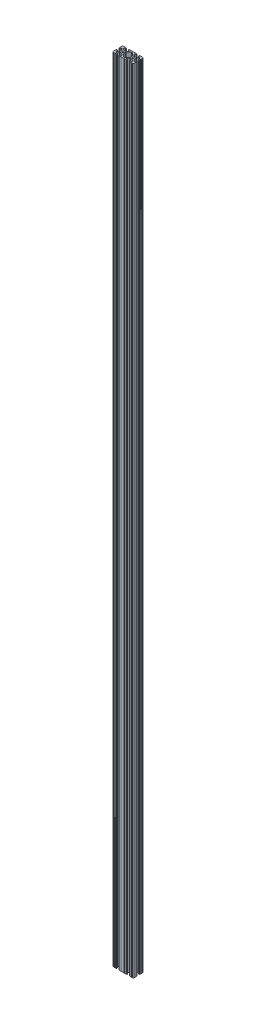
SolidWorks part; units mm, degrees
ref_plane "Piano frontale" through (0, 0, 0) normal (0, 0, 1) x (1, 0, 0)
ref_plane "Piano superiore" through (0, 0, 0) normal (0, 1, 0) x (1, 0, 0)
ref_plane "Piano destro" through (0, 0, 0) normal (1, 0, 0) x (0, 0, -1)
ref_plane "Piano1" through (0, 101.6, 0) normal (0, 1, 0) x (1, 0, 0)
sketch "Schizzo1" plane through (0, 101.6, 0) normal (0, 1, 0) x (1, 0, 0)
  line L0 (38.2382, -84.836) -> (37.9618, -84.836)
  line L1 (36.1657, -84.0921) -> (26.5503, -74.4767)
  line L2 (25.8064, -72.6806) -> (25.8064, -67.0194)
  line L3 (26.5503, -65.2233) -> (36.1657, -55.6079)
  line L4 (37.9618, -54.864) -> (38.2382, -54.864)
  line L5 (40.0343, -55.6079) -> (49.6497, -65.2233)
  line L6 (50.3936, -67.0194) -> (50.3936, -72.6806)
  line L7 (49.6497, -74.4767) -> (40.0343, -84.0921)
  line L8 (65.5208, -50.8) -> (62.992, -50.8)
  line L9 (61.214, -52.578) -> (61.214, -53.086)
  line L10 (62.992, -54.864) -> (66.8095, -54.864)
  line L11 (67.5279, -56.5984) -> (61.7767, -62.3497)
  line L12 (59.9806, -63.0936) -> (54.3194, -63.0936)
  line L13 (52.5233, -62.3497) -> (46.7721, -56.5984)
  line L14 (47.4905, -54.864) -> (51.308, -54.864)
  line L15 (53.086, -53.086) -> (53.086, -52.578)
  line L16 (51.308, -50.8) -> (48.641, -50.8)
  line L17 (47.879, -50.8) -> (43.561, -50.8)
  line L18 (42.799, -50.8) -> (33.401, -50.8)
  line L19 (32.639, -50.8) -> (28.321, -50.8)
  line L20 (27.559, -50.8) -> (24.892, -50.8)
  line L21 (23.114, -52.578) -> (23.114, -53.086)
  line L22 (24.892, -54.864) -> (28.7095, -54.864)
  line L23 (29.4279, -56.5984) -> (23.6767, -62.3497)
  line L24 (21.8806, -63.0936) -> (16.2194, -63.0936)
  line L25 (14.4233, -62.3497) -> (8.6721, -56.5984)
  line L26 (9.3905, -54.864) -> (13.208, -54.864)
  line L27 (14.986, -53.086) -> (14.986, -52.578)
  line L28 (13.208, -50.8) -> (10.4028, -50.8)
  line L29 (9.6408, -50.8) -> (5.3228, -50.8)
  line L30 (4.5608, -50.8) -> (2.54, -50.8)
  line L31 (0, -53.34) -> (0, -55.499)
  line L32 (0, -56.261) -> (0, -60.579)
  line L33 (0, -61.341) -> (0, -64.008)
  line L34 (1.778, -65.786) -> (2.286, -65.786)
  line L35 (4.064, -64.008) -> (4.064, -60.1905)
  line L36 (5.7984, -59.4721) -> (11.5497, -65.2233)
  line L37 (12.2936, -67.0194) -> (12.2936, -72.6806)
  line L38 (11.5497, -74.4767) -> (5.7984, -80.2279)
  line L39 (4.064, -79.5095) -> (4.064, -75.692)
  line L40 (2.286, -73.914) -> (1.778, -73.914)
  line L41 (0, -75.692) -> (0, -78.4972)
  line L42 (0, -79.2592) -> (0, -83.5772)
  line L43 (0, -84.3392) -> (0, -86.36)
  line L44 (2.54, -88.9) -> (4.699, -88.9)
  line L45 (5.461, -88.9) -> (9.779, -88.9)
  line L46 (10.541, -88.9) -> (13.208, -88.9)
  line L47 (14.986, -87.122) -> (14.986, -86.614)
  line L48 (13.208, -84.836) -> (9.3905, -84.836)
  line L49 (8.6721, -83.1016) -> (14.4233, -77.3503)
  line L50 (16.2194, -76.6064) -> (21.8806, -76.6064)
  line L51 (23.6767, -77.3503) -> (29.4279, -83.1016)
  line L52 (28.7095, -84.836) -> (24.892, -84.836)
  line L53 (23.114, -86.614) -> (23.114, -87.122)
  line L54 (24.892, -88.9) -> (27.6972, -88.9)
  line L55 (28.4592, -88.9) -> (32.7772, -88.9)
  line L56 (33.5392, -88.9) -> (42.9372, -88.9)
  line L57 (43.6992, -88.9) -> (48.0172, -88.9)
  line L58 (48.7792, -88.9) -> (51.308, -88.9)
  line L59 (53.086, -87.122) -> (53.086, -86.614)
  line L60 (51.308, -84.836) -> (47.4905, -84.836)
  line L61 (46.7721, -83.1016) -> (52.5233, -77.3503)
  line L62 (54.3194, -76.6064) -> (59.9806, -76.6064)
  line L63 (61.7767, -77.3503) -> (67.5279, -83.1016)
  line L64 (66.8095, -84.836) -> (62.992, -84.836)
  line L65 (61.214, -86.614) -> (61.214, -87.122)
  line L66 (62.992, -88.9) -> (65.659, -88.9)
  line L67 (66.421, -88.9) -> (70.739, -88.9)
  line L68 (71.501, -88.9) -> (73.66, -88.9)
  line L69 (76.2, -86.36) -> (76.2, -84.0628)
  line L70 (76.2, -83.3008) -> (76.2, -78.9828)
  line L71 (76.2, -78.2208) -> (76.2, -75.692)
  line L72 (74.422, -73.914) -> (73.914, -73.914)
  line L73 (72.136, -75.692) -> (72.136, -79.5095)
  line L74 (70.4016, -80.2279) -> (64.6503, -74.4767)
  line L75 (63.9064, -72.6806) -> (63.9064, -67.0194)
  line L76 (64.6503, -65.2233) -> (70.4016, -59.4721)
  line L77 (72.136, -60.1905) -> (72.136, -64.008)
  line L78 (73.914, -65.786) -> (74.422, -65.786)
  line L79 (76.2, -64.008) -> (76.2, -61.341)
  line L80 (76.2, -60.579) -> (76.2, -56.261)
  line L81 (76.2, -55.499) -> (76.2, -53.34)
  line L82 (73.66, -50.8) -> (71.3628, -50.8)
  line L83 (70.6008, -50.8) -> (66.2828, -50.8)
  arc A0 (37.9618, -84.836) -> (36.1657, -84.0921) centre (37.9618, -82.296) cw
  arc A1 (26.5503, -74.4767) -> (25.8064, -72.6806) centre (28.3464, -72.6806) cw
  arc A2 (25.8064, -67.0194) -> (26.5503, -65.2233) centre (28.3464, -67.0194) cw
  arc A3 (36.1657, -55.6079) -> (37.9618, -54.864) centre (37.9618, -57.404) cw
  arc A4 (38.2382, -54.864) -> (40.0343, -55.6079) centre (38.2382, -57.404) cw
  arc A5 (49.6497, -65.2233) -> (50.3936, -67.0194) centre (47.8536, -67.0194) cw
  arc A6 (50.3936, -72.6806) -> (49.6497, -74.4767) centre (47.8536, -72.6806) cw
  arc A7 (40.0343, -84.0921) -> (38.2382, -84.836) centre (38.2382, -82.296) cw
  circle A8 centre (57.15, -69.85) radius 3.3274
  circle A9 centre (19.05, -69.85) radius 3.3274
  arc A10 (66.2828, -50.8) -> (65.5208, -50.8) centre (65.9018, -50.8) cw
  arc A11 (62.992, -50.8) -> (61.214, -52.578) centre (62.992, -52.578) ccw
  arc A12 (61.214, -53.086) -> (62.992, -54.864) centre (62.992, -53.086) ccw
  arc A13 (66.8095, -54.864) -> (67.5279, -56.5984) centre (66.8095, -55.88) cw
  arc A14 (61.7767, -62.3497) -> (59.9806, -63.0936) centre (59.9806, -60.5536) cw
  arc A15 (54.3194, -63.0936) -> (52.5233, -62.3497) centre (54.3194, -60.5536) cw
  arc A16 (46.7721, -56.5984) -> (47.4905, -54.864) centre (47.4905, -55.88) cw
  arc A17 (51.308, -54.864) -> (53.086, -53.086) centre (51.308, -53.086) ccw
  arc A18 (53.086, -52.578) -> (51.308, -50.8) centre (51.308, -52.578) ccw
  arc A19 (48.641, -50.8) -> (47.879, -50.8) centre (48.26, -50.8) cw
  arc A20 (43.561, -50.8) -> (42.799, -50.8) centre (43.18, -50.8) cw
  arc A21 (33.401, -50.8) -> (32.639, -50.8) centre (33.02, -50.8) cw
  arc A22 (28.321, -50.8) -> (27.559, -50.8) centre (27.94, -50.8) cw
  arc A23 (24.892, -50.8) -> (23.114, -52.578) centre (24.892, -52.578) ccw
  arc A24 (23.114, -53.086) -> (24.892, -54.864) centre (24.892, -53.086) ccw
  arc A25 (28.7095, -54.864) -> (29.4279, -56.5984) centre (28.7095, -55.88) cw
  arc A26 (23.6767, -62.3497) -> (21.8806, -63.0936) centre (21.8806, -60.5536) cw
  arc A27 (16.2194, -63.0936) -> (14.4233, -62.3497) centre (16.2194, -60.5536) cw
  arc A28 (8.6721, -56.5984) -> (9.3905, -54.864) centre (9.3905, -55.88) cw
  arc A29 (13.208, -54.864) -> (14.986, -53.086) centre (13.208, -53.086) ccw
  arc A30 (14.986, -52.578) -> (13.208, -50.8) centre (13.208, -52.578) ccw
  arc A31 (10.4028, -50.8) -> (9.6408, -50.8) centre (10.0218, -50.8) cw
  arc A32 (5.3228, -50.8) -> (4.5608, -50.8) centre (4.9418, -50.8) cw
  arc A33 (2.54, -50.8) -> (0, -53.34) centre (2.54, -53.34) ccw
  arc A34 (0, -55.499) -> (0, -56.261) centre (0, -55.88) cw
  arc A35 (0, -60.579) -> (0, -61.341) centre (0, -60.96) cw
  arc A36 (0, -64.008) -> (1.778, -65.786) centre (1.778, -64.008) ccw
  arc A37 (2.286, -65.786) -> (4.064, -64.008) centre (2.286, -64.008) ccw
  arc A38 (4.064, -60.1905) -> (5.7984, -59.4721) centre (5.08, -60.1905) cw
  arc A39 (11.5497, -65.2233) -> (12.2936, -67.0194) centre (9.7536, -67.0194) cw
  arc A40 (12.2936, -72.6806) -> (11.5497, -74.4767) centre (9.7536, -72.6806) cw
  arc A41 (5.7984, -80.2279) -> (4.064, -79.5095) centre (5.08, -79.5095) cw
  arc A42 (4.064, -75.692) -> (2.286, -73.914) centre (2.286, -75.692) ccw
  arc A43 (1.778, -73.914) -> (0, -75.692) centre (1.778, -75.692) ccw
  arc A44 (0, -78.4972) -> (0, -79.2592) centre (0, -78.8782) cw
  arc A45 (0, -83.5772) -> (0, -84.3392) centre (0, -83.9582) cw
  arc A46 (0, -86.36) -> (2.54, -88.9) centre (2.54, -86.36) ccw
  arc A47 (4.699, -88.9) -> (5.461, -88.9) centre (5.08, -88.9) cw
  arc A48 (9.779, -88.9) -> (10.541, -88.9) centre (10.16, -88.9) cw
  arc A49 (13.208, -88.9) -> (14.986, -87.122) centre (13.208, -87.122) ccw
  arc A50 (14.986, -86.614) -> (13.208, -84.836) centre (13.208, -86.614) ccw
  arc A51 (9.3905, -84.836) -> (8.6721, -83.1016) centre (9.3905, -83.82) cw
  arc A52 (14.4233, -77.3503) -> (16.2194, -76.6064) centre (16.2194, -79.1464) cw
  arc A53 (21.8806, -76.6064) -> (23.6767, -77.3503) centre (21.8806, -79.1464) cw
  arc A54 (29.4279, -83.1016) -> (28.7095, -84.836) centre (28.7095, -83.82) cw
  arc A55 (24.892, -84.836) -> (23.114, -86.614) centre (24.892, -86.614) ccw
  arc A56 (23.114, -87.122) -> (24.892, -88.9) centre (24.892, -87.122) ccw
  arc A57 (27.6972, -88.9) -> (28.4592, -88.9) centre (28.0782, -88.9) cw
  arc A58 (32.7772, -88.9) -> (33.5392, -88.9) centre (33.1582, -88.9) cw
  arc A59 (42.9372, -88.9) -> (43.6992, -88.9) centre (43.3182, -88.9) cw
  arc A60 (48.0172, -88.9) -> (48.7792, -88.9) centre (48.3982, -88.9) cw
  arc A61 (51.308, -88.9) -> (53.086, -87.122) centre (51.308, -87.122) ccw
  arc A62 (53.086, -86.614) -> (51.308, -84.836) centre (51.308, -86.614) ccw
  arc A63 (47.4905, -84.836) -> (46.7721, -83.1016) centre (47.4905, -83.82) cw
  arc A64 (52.5233, -77.3503) -> (54.3194, -76.6064) centre (54.3194, -79.1464) cw
  arc A65 (59.9806, -76.6064) -> (61.7767, -77.3503) centre (59.9806, -79.1464) cw
  arc A66 (67.5279, -83.1016) -> (66.8095, -84.836) centre (66.8095, -83.82) cw
  arc A67 (62.992, -84.836) -> (61.214, -86.614) centre (62.992, -86.614) ccw
  arc A68 (61.214, -87.122) -> (62.992, -88.9) centre (62.992, -87.122) ccw
  arc A69 (65.659, -88.9) -> (66.421, -88.9) centre (66.04, -88.9) cw
  arc A70 (70.739, -88.9) -> (71.501, -88.9) centre (71.12, -88.9) cw
  arc A71 (73.66, -88.9) -> (76.2, -86.36) centre (73.66, -86.36) ccw
  arc A72 (76.2, -84.0628) -> (76.2, -83.3008) centre (76.2, -83.6818) cw
  arc A73 (76.2, -78.9828) -> (76.2, -78.2208) centre (76.2, -78.6018) cw
  arc A74 (76.2, -75.692) -> (74.422, -73.914) centre (74.422, -75.692) ccw
  arc A75 (73.914, -73.914) -> (72.136, -75.692) centre (73.914, -75.692) ccw
  arc A76 (72.136, -79.5095) -> (70.4016, -80.2279) centre (71.12, -79.5095) cw
  arc A77 (64.6503, -74.4767) -> (63.9064, -72.6806) centre (66.4464, -72.6806) cw
  arc A78 (63.9064, -67.0194) -> (64.6503, -65.2233) centre (66.4464, -67.0194) cw
  arc A79 (70.4016, -59.4721) -> (72.136, -60.1905) centre (71.12, -60.1905) cw
  arc A80 (72.136, -64.008) -> (73.914, -65.786) centre (73.914, -64.008) ccw
  arc A81 (74.422, -65.786) -> (76.2, -64.008) centre (74.422, -64.008) ccw
  arc A82 (76.2, -61.341) -> (76.2, -60.579) centre (76.2, -60.96) cw
  arc A83 (76.2, -56.261) -> (76.2, -55.499) centre (76.2, -55.88) cw
  arc A84 (76.2, -53.34) -> (73.66, -50.8) centre (73.66, -53.34) ccw
  arc A85 (71.3628, -50.8) -> (70.6008, -50.8) centre (70.9818, -50.8) cw
extrude "Estrusione-Estrusione1" add sketch "Schizzo1" against normal blind 2900
